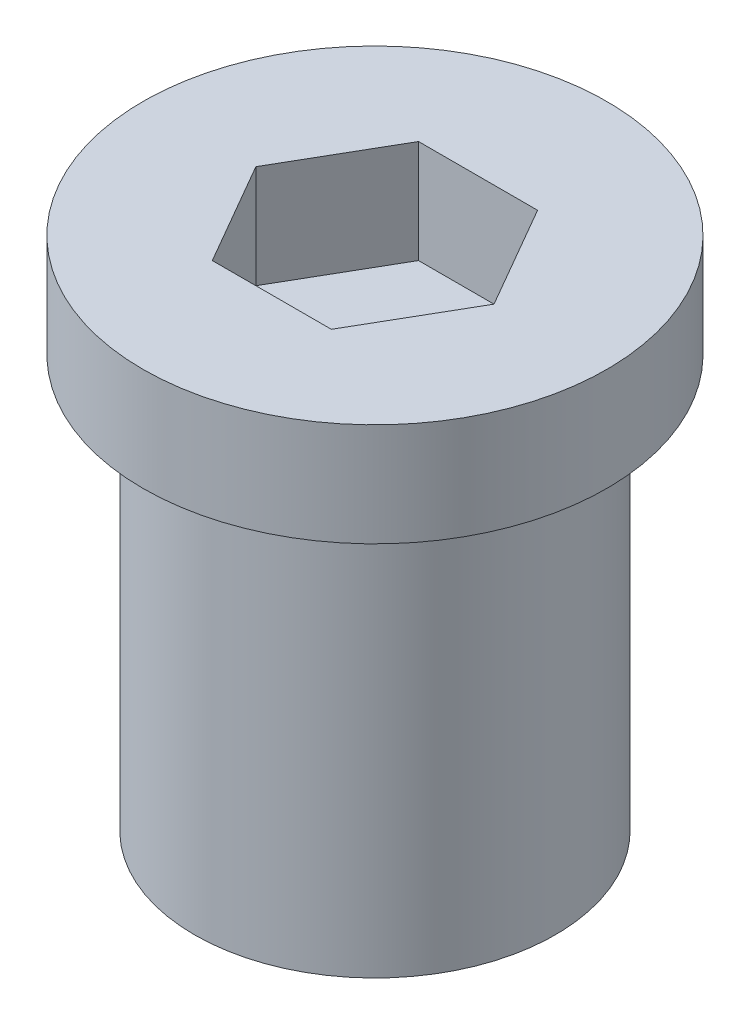
SolidWorks part; units mm, degrees
material "AISI 304"
ref_plane "Front Plane" through (0, 0, 0) normal (0, 0, 1) x (1, 0, 0)
ref_plane "Top Plane" through (0, 0, 0) normal (0, 1, 0) x (1, 0, 0)
ref_plane "Right Plane" through (0, 0, 0) normal (1, 0, 0) x (0, 0, -1)
sketch "Sketch1" plane through (0, 0, 0) normal (0, 1, 0) x (1, 0, 0)
  circle A0 centre (0, 0) radius 1.75
  dimension "D1" = 3.5
extrude "Boss-Extrude1" add sketch "Sketch1" along normal mid plane 4
sketch "Sketch2" plane through (0, 2, 0) normal (0, 1, 0) x (1, 0, 0)
  circle A0 centre (0, 0) radius 2.25
  dimension "D1" = 4.5
extrude "Boss-Extrude2" add sketch "Sketch2" along normal blind 1
sketch "Sketch3" plane through (0, 3, 0) normal (0, 1, 0) x (1, 0, 0)
  line L0 (1.1547, 0) -> (0.5774, 1)
  line L1 (0.5774, 1) -> (-0.5774, 1)
  line L2 (-0.5774, 1) -> (-1.1547, 0)
  line L3 (-1.1547, 0) -> (-0.5774, -1)
  line L4 (-0.5774, -1) -> (0.5774, -1)
  line L5 (0.5774, -1) -> (1.1547, 0)
  circle A0 centre (0, 0) radius 1 construction
  dimension "D1" = 2
  dimension "D2" = 1.1547
  dimension "D3" = 1
  dimension "D4" = 1.1547
extrude "Cut-Extrude1" cut sketch "Sketch3" against normal blind 1
